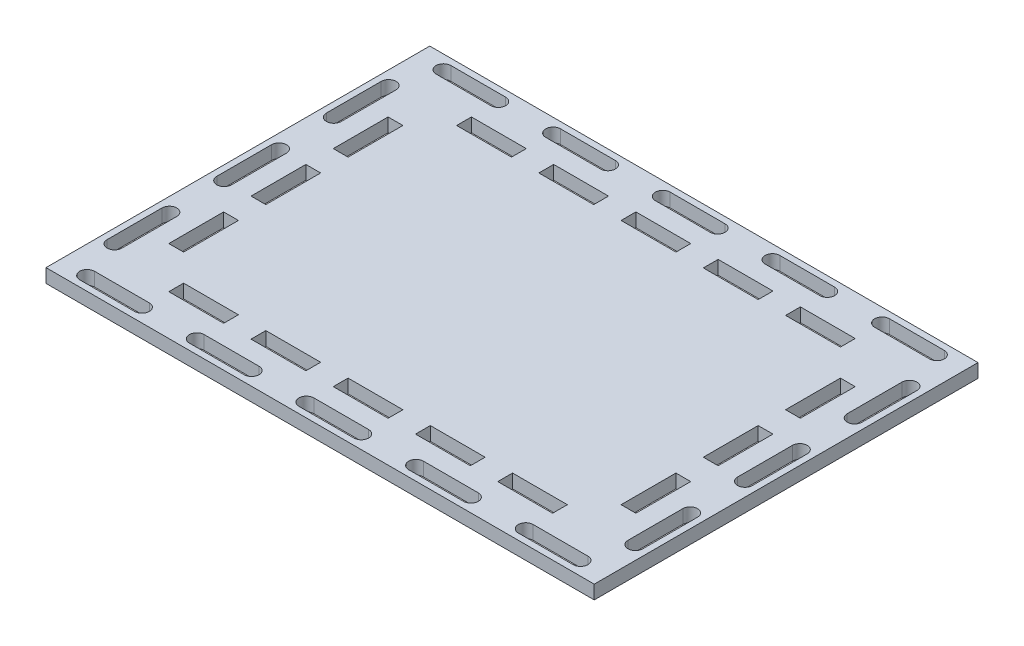
SolidWorks part; units mm, degrees
ref_plane "Front Plane" through (0, 0, 0) normal (0, 0, 1) x (1, 0, 0)
ref_plane "Top Plane" through (0, 0, 0) normal (0, 1, 0) x (1, 0, 0)
ref_plane "Right Plane" through (0, 0, 0) normal (1, 0, 0) x (0, 0, -1)
sketch "Sketch1" plane through (0, 0, 0) normal (0, 1, 0) x (1, 0, 0)
  line L1 (-127, -88.9) -> (127, -88.9)
  line L2 (-127, -88.9) -> (-127, 88.9)
  line L3 (-127, 88.9) -> (127, 88.9)
  line L4 (127, -88.9) -> (127, 88.9)
  line L5 (-127, -88.9) -> (127, 88.9) construction
  line L6 (-127, 88.9) -> (127, -88.9) construction
  point P0 (0, 0)
  dimension "D1" = 254
  dimension "D2" = 177.8
extrude "Boss-Extrude1" add sketch "Sketch1" along normal blind 6.35
sketch "Sketch2" plane through (0, 0, 0) normal (0, 1, 0) x (1, 0, 0)
  line L50 (88.9, 70.104) -> (88.9, 63.246)
  line L51 (63.5, 63.246) -> (88.9, 63.246)
  line L52 (63.5, 70.104) -> (63.5, 63.246)
  line L53 (63.5, 70.104) -> (88.9, 70.104)
  line L54 (-88.9, 63.246) -> (-63.5, 63.246)
  line L55 (-63.5, 70.104) -> (-63.5, 63.246)
  line L56 (-88.9, 70.104) -> (-63.5, 70.104)
  line L57 (-88.9, 70.104) -> (-88.9, 63.246)
  line L58 (38.1, 85.979) -> (63.5, 85.979)
  line L59 (63.5, 79.121) -> (38.1, 79.121)
  line L60 (88.9, 85.979) -> (114.3, 85.979)
  line L61 (114.3, 79.121) -> (88.9, 79.121)
  line L64 (0, 0) -> (0, -88.9) construction
  line L65 (-127, -88.9) -> (127, -88.9) construction
  line L66 (0, 0) -> (127, 0) construction
  line L67 (127, -88.9) -> (127, 88.9) construction
  line L68 (127, 88.9) -> (-127, 88.9) construction
  line L116 (-114.3, 85.979) -> (-88.9, 85.979)
  line L117 (25.4, 70.104) -> (50.8, 70.104)
  line L154 (-63.5, 85.979) -> (-38.1, 85.979)
  line L155 (-127, 88.9) -> (-127, -88.9) construction
  line L168 (-88.9, 79.121) -> (-114.3, 79.121)
  line L169 (-38.1, 79.121) -> (-63.5, 79.121)
  line L170 (-12.7, 85.979) -> (12.7, 85.979)
  line L171 (12.7, 79.121) -> (-12.7, 79.121)
  line L202 (-101.346, 50.8) -> (-101.346, 25.4)
  line L203 (-108.204, 12.7) -> (-101.346, 12.7)
  line L204 (38.1, 85.979) -> (63.5, 85.979) [skipped]
  line L205 (63.5, 79.121) -> (38.1, 79.121) [skipped]
  line L209 (-108.204, 12.7) -> (-108.204, -12.7)
  line L210 (-108.204, -12.7) -> (-101.346, -12.7)
  line L211 (50.8, 70.104) -> (50.8, 63.246)
  line L212 (25.4, 63.246) -> (50.8, 63.246)
  line L213 (-12.7, 70.104) -> (12.7, 70.104)
  line L214 (-12.7, 70.104) -> (-12.7, 63.246)
  line L215 (-12.7, 63.246) -> (12.7, 63.246)
  line L216 (12.7, 70.104) -> (12.7, 63.246)
  line L217 (-101.346, 12.7) -> (-101.346, -12.7)
  line L218 (88.9, 85.979) -> (114.3, 85.979) [skipped]
  line L219 (114.3, 79.121) -> (88.9, 79.121) [skipped]
  line L220 (139.7, 85.979) -> (165.1, 85.979) [skipped]
  line L221 (165.1, 79.121) -> (139.7, 79.121) [skipped]
  line L222 (25.4, 70.104) -> (25.4, 63.246)
  line L223 (-50.8, 70.104) -> (-25.4, 70.104)
  line L224 (-25.4, 70.104) -> (-25.4, 63.246)
  line L225 (-50.8, 63.246) -> (-25.4, 63.246)
  line L226 (-50.8, 70.104) -> (-50.8, 63.246)
  line L227 (-108.204, 25.4) -> (-101.346, 25.4)
  line L228 (-120.65, -12.7) -> (-120.65, 12.7) construction
  line L245 (-108.204, 50.8) -> (-108.204, 25.4)
  line L246 (-124.079, -12.7) -> (-124.079, 12.7)
  line L283 (-108.204, 50.8) -> (-101.346, 50.8)
  line L284 (-101.346, -25.4) -> (-101.346, -50.8)
  line L285 (-108.204, -50.8) -> (-101.346, -50.8)
  line L286 (-108.204, -25.4) -> (-108.204, -50.8)
  line L287 (-108.204, -25.4) -> (-101.346, -25.4)
  line L288 (-117.221, -12.7) -> (-117.221, 12.7)
  line L289 (-120.65, 38.1) -> (-120.65, 63.5) construction
  line L290 (-124.079, 38.1) -> (-124.079, 63.5)
  line L291 (-117.221, 38.1) -> (-117.221, 63.5)
  line L292 (-120.65, -63.5) -> (-120.65, -38.1) construction
  line L293 (-124.079, -63.5) -> (-124.079, -38.1)
  line L294 (-117.221, -63.5) -> (-117.221, -38.1)
  line L295 (120.65, -12.7) -> (120.65, 12.7) construction
  line L296 (124.079, -12.7) -> (124.079, 12.7)
  line L297 (117.221, -12.7) -> (117.221, 12.7)
  line L298 (120.65, 38.1) -> (120.65, 63.5) construction
  line L299 (124.079, 38.1) -> (124.079, 63.5)
  line L300 (117.221, 38.1) -> (117.221, 63.5)
  line L301 (120.65, -63.5) -> (120.65, -38.1) construction
  line L302 (124.079, -63.5) -> (124.079, -38.1)
  line L303 (117.221, -63.5) -> (117.221, -38.1)
  line L304 (108.204, -25.4) -> (101.346, -25.4)
  line L305 (108.204, -25.4) -> (108.204, -50.8)
  line L306 (108.204, -50.8) -> (101.346, -50.8)
  line L307 (101.346, -25.4) -> (101.346, -50.8)
  line L308 (108.204, 50.8) -> (101.346, 50.8)
  line L309 (108.204, 50.8) -> (108.204, 25.4)
  line L310 (108.204, 25.4) -> (101.346, 25.4)
  line L311 (101.346, 12.7) -> (101.346, -12.7)
  line L312 (108.204, -12.7) -> (101.346, -12.7)
  line L313 (108.204, 12.7) -> (108.204, -12.7)
  line L314 (108.204, 12.7) -> (101.346, 12.7)
  line L315 (101.346, 50.8) -> (101.346, 25.4)
  line L316 (-50.8, -70.104) -> (-50.8, -63.246)
  line L317 (-50.8, -63.246) -> (-25.4, -63.246)
  line L318 (-25.4, -70.104) -> (-25.4, -63.246)
  line L319 (-50.8, -70.104) -> (-25.4, -70.104)
  line L320 (25.4, -70.104) -> (25.4, -63.246)
  line L321 (12.7, -70.104) -> (12.7, -63.246)
  line L322 (-12.7, -63.246) -> (12.7, -63.246)
  line L323 (-12.7, -70.104) -> (-12.7, -63.246)
  line L324 (-12.7, -70.104) -> (12.7, -70.104)
  line L325 (25.4, -63.246) -> (50.8, -63.246)
  line L326 (50.8, -70.104) -> (50.8, -63.246)
  line L327 (12.7, -79.121) -> (-12.7, -79.121)
  line L328 (-12.7, -85.979) -> (12.7, -85.979)
  line L329 (-38.1, -79.121) -> (-63.5, -79.121)
  line L330 (-88.9, -79.121) -> (-114.3, -79.121)
  line L331 (-63.5, -85.979) -> (-38.1, -85.979)
  line L332 (25.4, -70.104) -> (50.8, -70.104)
  line L333 (-114.3, -85.979) -> (-88.9, -85.979)
  line L334 (114.3, -79.121) -> (88.9, -79.121)
  line L335 (88.9, -85.979) -> (114.3, -85.979)
  line L336 (63.5, -79.121) -> (38.1, -79.121)
  line L337 (38.1, -85.979) -> (63.5, -85.979)
  line L338 (-88.9, -70.104) -> (-88.9, -63.246)
  line L339 (-88.9, -70.104) -> (-63.5, -70.104)
  line L340 (-63.5, -70.104) -> (-63.5, -63.246)
  line L341 (-88.9, -63.246) -> (-63.5, -63.246)
  line L342 (63.5, -70.104) -> (88.9, -70.104)
  line L343 (63.5, -70.104) -> (63.5, -63.246)
  line L344 (63.5, -63.246) -> (88.9, -63.246)
  line L345 (88.9, -70.104) -> (88.9, -63.246)
  arc A69 (-114.3, 85.979) -> (-114.3, 79.121) centre (-114.3, 82.55) ccw
  arc A70 (-88.9, 79.121) -> (-88.9, 85.979) centre (-88.9, 82.55) ccw
  arc A71 (-38.1, 79.121) -> (-38.1, 85.979) centre (-38.1, 82.55) ccw
  arc A72 (-63.5, 85.979) -> (-63.5, 79.121) centre (-63.5, 82.55) ccw
  arc A73 (12.7, 79.121) -> (12.7, 85.979) centre (12.7, 82.55) ccw
  arc A74 (-12.7, 85.979) -> (-12.7, 79.121) centre (-12.7, 82.55) ccw
  arc A105 (63.5, 79.121) -> (63.5, 85.979) centre (63.5, 82.55) ccw
  arc A106 (38.1, 85.979) -> (38.1, 79.121) centre (38.1, 82.55) ccw
  arc A107 (63.5, 79.121) -> (63.5, 85.979) centre (63.5, 82.55) ccw [skipped]
  arc A108 (38.1, 85.979) -> (38.1, 79.121) centre (38.1, 82.55) ccw [skipped]
  arc A113 (114.3, 79.121) -> (114.3, 85.979) centre (114.3, 82.55) ccw [skipped]
  arc A114 (88.9, 85.979) -> (88.9, 79.121) centre (88.9, 82.55) ccw [skipped]
  arc A115 (165.1, 79.121) -> (165.1, 85.979) centre (165.1, 82.55) ccw [skipped]
  arc A116 (139.7, 85.979) -> (139.7, 79.121) centre (139.7, 82.55) ccw [skipped]
  arc A124 (114.3, 79.121) -> (114.3, 85.979) centre (114.3, 82.55) ccw
  arc A125 (88.9, 85.979) -> (88.9, 79.121) centre (88.9, 82.55) ccw
  arc A126 (-124.079, -12.7) -> (-117.221, -12.7) centre (-120.65, -12.7) ccw
  arc A127 (-117.221, 12.7) -> (-124.079, 12.7) centre (-120.65, 12.7) ccw
  arc A128 (-124.079, 38.1) -> (-117.221, 38.1) centre (-120.65, 38.1) ccw
  arc A129 (-117.221, 63.5) -> (-124.079, 63.5) centre (-120.65, 63.5) ccw
  arc A130 (-124.079, -63.5) -> (-117.221, -63.5) centre (-120.65, -63.5) ccw
  arc A131 (-117.221, -38.1) -> (-124.079, -38.1) centre (-120.65, -38.1) ccw
  arc A132 (124.079, -12.7) -> (117.221, -12.7) centre (120.65, -12.7) cw
  arc A133 (117.221, 12.7) -> (124.079, 12.7) centre (120.65, 12.7) cw
  arc A134 (124.079, 38.1) -> (117.221, 38.1) centre (120.65, 38.1) cw
  arc A135 (117.221, 63.5) -> (124.079, 63.5) centre (120.65, 63.5) cw
  arc A136 (124.079, -63.5) -> (117.221, -63.5) centre (120.65, -63.5) cw
  arc A137 (117.221, -38.1) -> (124.079, -38.1) centre (120.65, -38.1) cw
  arc A138 (88.9, -85.979) -> (88.9, -79.121) centre (88.9, -82.55) cw
  arc A139 (114.3, -79.121) -> (114.3, -85.979) centre (114.3, -82.55) cw
  arc A140 (38.1, -85.979) -> (38.1, -79.121) centre (38.1, -82.55) cw
  arc A141 (63.5, -79.121) -> (63.5, -85.979) centre (63.5, -82.55) cw
  arc A142 (-12.7, -85.979) -> (-12.7, -79.121) centre (-12.7, -82.55) cw
  arc A143 (12.7, -79.121) -> (12.7, -85.979) centre (12.7, -82.55) cw
  arc A144 (-63.5, -85.979) -> (-63.5, -79.121) centre (-63.5, -82.55) cw
  arc A145 (-38.1, -79.121) -> (-38.1, -85.979) centre (-38.1, -82.55) cw
  arc A146 (-88.9, -79.121) -> (-88.9, -85.979) centre (-88.9, -82.55) cw
  arc A147 (-114.3, -85.979) -> (-114.3, -79.121) centre (-114.3, -82.55) cw
  point P30 (-101.346, 0)
  point P62 (-120.65, 0)
  point P70 (-120.65, 50.8)
  point P78 (-120.65, -50.8)
  point P88 (120.65, 0)
  point P91 (0, 63.246)
  point P96 (120.65, 50.8)
  point P103 (120.65, -50.8)
  dimension "D5" = 6.858
  dimension "D2" = 25.4
  dimension "D3" = 2
  dimension "D4" = 2
  dimension "D6" = 6.35
  dimension "D7" = 2
  dimension "D10" = 101.346
  dimension "D12" = 12.7
  dimension "D14" = 25.4
  dimension "D15" = 2
  dimension "D8" = 2
  dimension "D17" = 6.858
  dimension "D18" = 63.246
  dimension "D16" = 6.35
  dimension "D20" = 12.7
  dimension "D21" = 12.7
  dimension "D13" = 6
  dimension "D9" = 3
  dimension "D11" = 2
  dimension "D19" = 2
  dimension "D22" = 2
extrude "Cut-Extrude1" cut sketch "Sketch2" along normal through all
